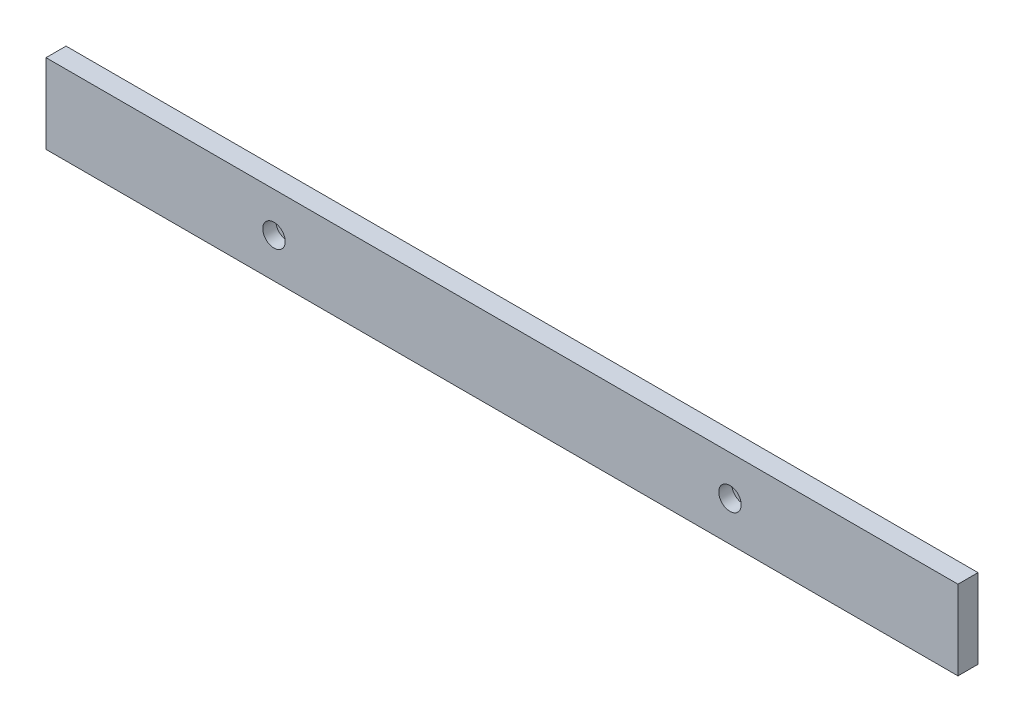
SolidWorks part; units mm, degrees
ref_plane "Front Plane" through (0, 0, 0) normal (0, 0, 1) x (1, 0, 0)
ref_plane "Top Plane" through (0, 0, 0) normal (0, 1, 0) x (1, 0, 0)
ref_plane "Right Plane" through (0, 0, 0) normal (1, 0, 0) x (0, 0, -1)
sketch "Sketch1" plane through (0, 0, 0) normal (0, 0, 1) x (1, 0, 0)
  line L0 (-132, 0) -> (-66, 0) construction
  line L1 (-132, 11.5) -> (132, 11.5)
  line L2 (-132, 11.5) -> (-132, -11.5)
  line L3 (-132, -11.5) -> (132, -11.5)
  line L4 (132, 11.5) -> (132, -11.5)
  line L5 (-132, 11.5) -> (132, -11.5) construction
  line L6 (-132, -11.5) -> (132, 11.5) construction
  line L7 (-66, 0) -> (0, 0) construction
  line L8 (0, 0) -> (66, 0) construction
  line L9 (66, 0) -> (132, 0) construction
  circle A0 centre (-66, 0) radius 1.5
  circle A1 centre (66, 0) radius 1.5
  point P0 (0, 0)
  dimension "D3" = 3
  dimension "D1" = 264
  dimension "D2" = 23
extrude "Boss-Extrude1" add sketch "Sketch1" along normal blind 5.8
sketch "Sketch2" plane through (0, 0, 5.8) normal (0, 0, 1) x (1, 0, 0)
  circle A0 centre (-66, 0) radius 3.25
  circle A1 centre (66, 0) radius 3.25
  dimension "D1" = 6.5
extrude "Cut-Extrude1" cut sketch "Sketch2" against normal offset from surface (3.8 mm away) 2 up to face at (0, 0, 0)
